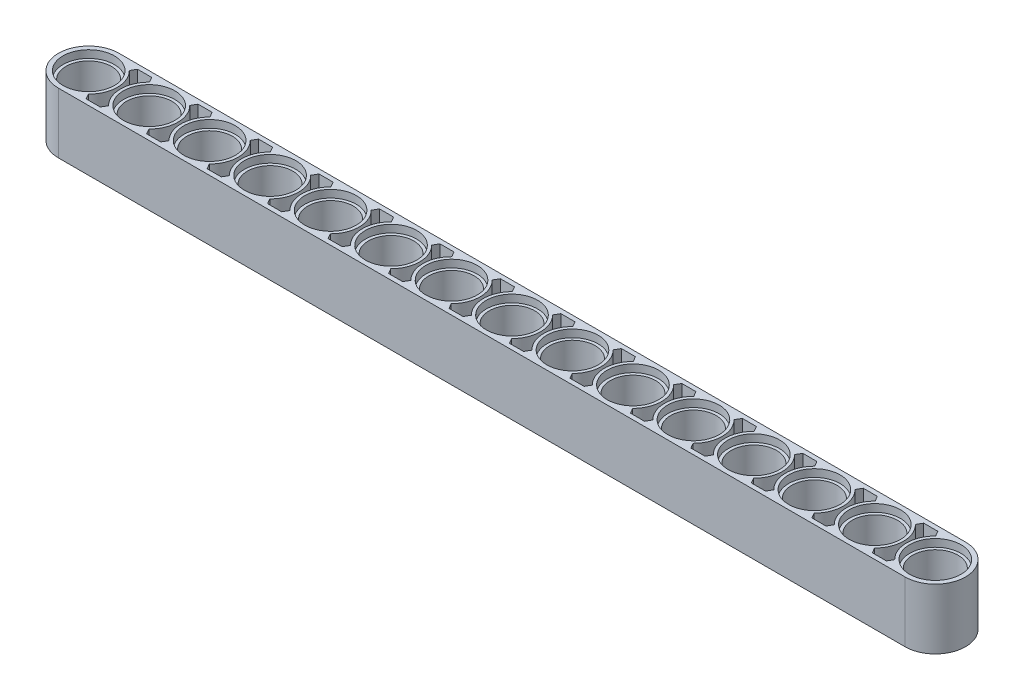
SolidWorks part; units mm, degrees
ref_plane "Front Plane" through (0, 0, 0) normal (0, 0, 1) x (1, 0, 0)
ref_plane "Top Plane" through (0, 0, 0) normal (0, 1, 0) x (1, 0, 0)
ref_plane "Right Plane" through (0, 0, 0) normal (1, 0, 0) x (0, 0, -1)
sketch "Sketch1" plane through (0, 0, 0) normal (0, 1, 0) x (1, 0, 0)
  line L0 (0, 0) -> (112, 0) construction
  line L1 (0, 4) -> (112, 4)
  line L2 (0, -4) -> (112, -4)
  arc A0 (0, 4) -> (0, -4) centre (0, 0) ccw
  arc A1 (112, -4) -> (112, 4) centre (112, 0) ccw
  circle A2 centre (8, 0) radius 3
  circle A3 centre (16, 0) radius 3
  circle A4 centre (0, 0) radius 3
  circle A5 centre (24, 0) radius 3
  circle A6 centre (32, 0) radius 3
  circle A7 centre (40, 0) radius 3
  circle A8 centre (48, 0) radius 3
  circle A9 centre (56, 0) radius 3
  circle A10 centre (64, 0) radius 3
  circle A11 centre (72, 0) radius 3
  circle A12 centre (80, 0) radius 3
  circle A13 centre (88, 0) radius 3
  circle A14 centre (96, 0) radius 3
  circle A15 centre (104, 0) radius 3
  circle A16 centre (112, 0) radius 3
  point P2 (-3, 0)
  point P3 (56, 0)
  point P8 (-4, 0)
  point P9 (116, 0)
  point P16 (3, 0)
  point P18 (5, 0)
  point P19 (11, 0)
  point P20 (13, 0)
  point P21 (19, 0)
  point P46 (21, 0)
  point P47 (27, 0)
  point P48 (29, 0)
  point P49 (35, 0)
  point P50 (37, 0)
  point P51 (43, 0)
  point P52 (45, 0)
  point P53 (51, 0)
  point P54 (53, 0)
  point P55 (59, 0)
  point P56 (61, 0)
  point P57 (67, 0)
  point P58 (69, 0)
  point P59 (75, 0)
  point P60 (77, 0)
  point P61 (83, 0)
  point P62 (85, 0)
  point P63 (91, 0)
  point P64 (93, 0)
  point P65 (99, 0)
  point P66 (101, 0)
  point P67 (107, 0)
  point P68 (109, 0)
  point P69 (115, 0)
  dimension "D2" = 20
  dimension "D3" = 6
  dimension "D4" = 6
  dimension "D5" = 6
  dimension "D6" = 4
  dimension "D9" = 6
  dimension "D10" = 6
  dimension "D11" = 6
  dimension "D18" = 6
  dimension "D19" = 6
  dimension "D20" = 6
  dimension "D22" = 6
  dimension "D23" = 6
  dimension "D25" = 6
  dimension "D27" = 6
  dimension "D28" = 6
  dimension "D29" = 6
  dimension "D1" = 120
  dimension "D7" = 1
  dimension "D8" = 2
  dimension "D12" = 2
  dimension "D13" = 2
  dimension "D14" = 2
  dimension "D15" = 2
  dimension "D16" = 2
  dimension "D17" = 2
  dimension "D21" = 1
  dimension "D24" = 2
  dimension "D26" = 2
  dimension "D30" = 2
  dimension "D31" = 2
  dimension "D32" = 2
extrude "Boss-Extrude1" add sketch "Sketch1" along normal blind 8
sketch "Sketch2" plane through (0, 8, 0) normal (0, 1, 0) x (1, 0, 0)
  circle A0 centre (0, 0) radius 3.4
  circle A1 centre (0, 0) radius 3
  dimension "D1" = 6.8
  dimension "D2" = 6
extrude "Cut-Extrude1" cut sketch "Sketch2" against normal blind 1
pattern_linear "LPattern1" count 15 spacing 8 along (1, 0, 0) count 2 spacing 7 along (0, -1, 0) of "Cut-Extrude1"
sketch "Sketch3" plane through (0, 8, 0) normal (0, 1, 0) x (1, 0, 0)
  line L0 (3.0667, -3.4) -> (4.9333, -3.4)
  line L1 (0, -4) -> (112, -4) construction
  line L2 (3.0667, 3.4) -> (4.9333, 3.4)
  line L3 (112, 4) -> (0, 4) construction
  line L4 (3.0667, 3.4) -> (2.6667, 2.7072)
  line L5 (4.9333, 3.4) -> (5.3333, 2.7072)
  line L6 (2.6667, -2.7072) -> (3.0667, -3.4)
  line L7 (5.3333, -2.7072) -> (4.9333, -3.4)
  arc A0 (2.6667, -2.7072) -> (2.6667, 2.7072) centre (0, 0) ccw
  arc A1 (5.3333, 2.7072) -> (5.3333, -2.7072) centre (8, 0) ccw
  dimension "D1" = 7.6
  dimension "D2" = 7.6
  dimension "D3" = 0.6
  dimension "D4" = 0.6
  dimension "D5" = 0.8
  dimension "D6" = 0.8
  dimension "D7" = 120
  dimension "D8" = 120
  dimension "D9" = 120
  dimension "D10" = 120
extrude "Cut-Extrude2" cut sketch "Sketch3" against normal blind 3
pattern_linear "LPattern2" count 14 spacing 8 along (1, 0, 0) count 2 spacing 5 along (0, -1, 0) of "Cut-Extrude2"
